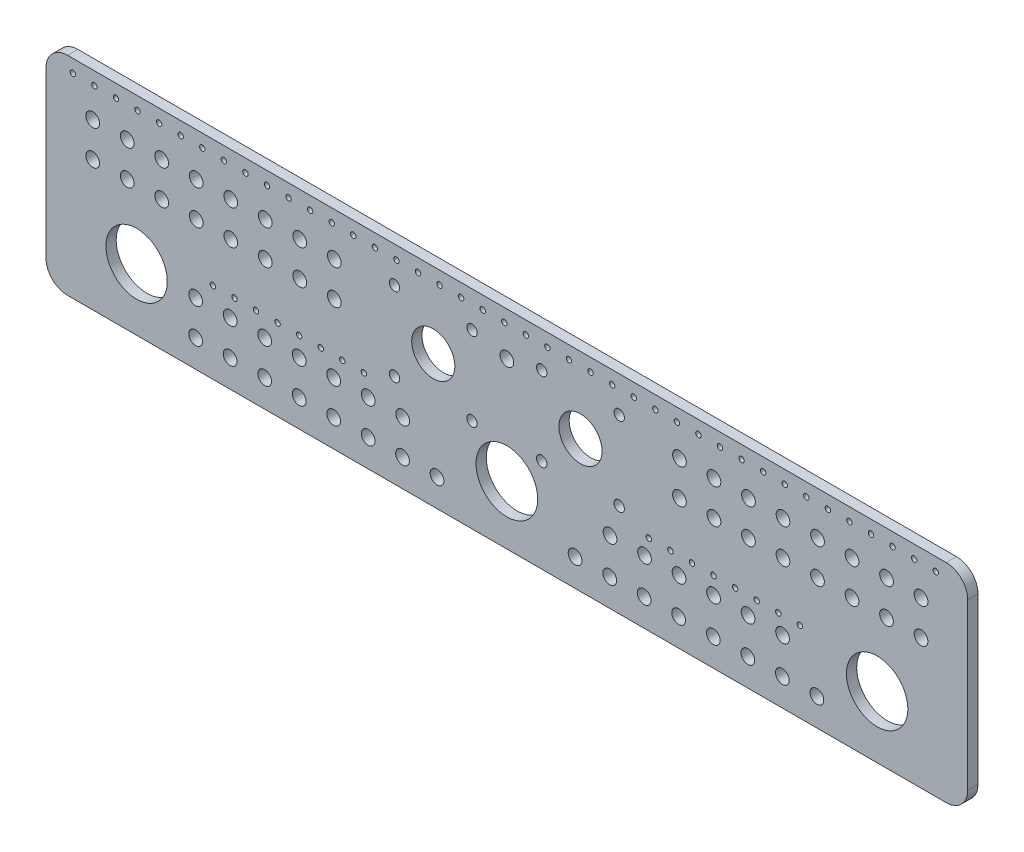
SolidWorks part; units mm, degrees
ref_plane "Front" through (0, 0, 0) normal (0, 0, 1) x (1, 0, 0)
ref_plane "Top" through (0, 0, 0) normal (0, 1, 0) x (1, 0, 0)
ref_plane "Right" through (0, 0, 0) normal (1, 0, 0) x (0, 0, -1)
sketch "Sketch1" plane through (0, 0, 0) normal (0, 0, 1) x (1, 0, 0)
  line L0 (-426.3498, 80.4904) -> (-19.0698, 80.4904)
  line L2 (-436.3498, 70.4904) -> (-436.3498, -5.9096)
  line L4 (-9.0698, 70.4904) -> (-9.0698, -5.9096)
  line L5 (-19.0698, -15.9096) -> (-426.3498, -15.9096)
  circle A0 centre (-394.3498, 12.7904) radius 14.225
  circle A1 centre (-51.0698, 12.7904) radius 14.225
  circle A11 centre (-222.7098, 11.2904) radius 14.3
  circle A54 centre (-174.8998, 13.3845) radius 3.18
  circle A151 centre (-366.9908, 12.7904) radius 3.18
  circle A155 centre (-358.9957, 21.7191) radius 1.25
  circle A159 centre (-94.8998, 13.3845) radius 3.18
  circle A181 centre (-366.9908, -3.2096) radius 3.18
  circle A190 centre (-94.9957, -3.2096) radius 3.18
  circle A191 centre (-110.9957, -3.2096) radius 3.18
  circle A192 centre (-126.9957, -3.2096) radius 3.18
  circle A193 centre (-78.9957, -3.2096) radius 3.18
  circle A194 centre (-143.0916, -3.2096) radius 3.18
  circle A195 centre (-159.0916, -3.2096) radius 3.18
  circle A196 centre (-174.9957, -3.2096) radius 3.18
  circle A279 centre (-96.8998, 21.3845) radius 1.25
  circle A285 centre (-106.8998, 21.3845) radius 1.25
  circle A286 centre (-350.9908, 12.7904) radius 3.18
  circle A287 centre (-350.9908, -3.2096) radius 3.18
  circle A288 centre (-334.9908, 12.7904) radius 3.18
  circle A289 centre (-334.9908, -3.2096) radius 3.18
  circle A290 centre (-318.9908, 12.7904) radius 3.18
  circle A291 centre (-318.9908, -3.2096) radius 3.18
  circle A292 centre (-302.9908, 12.7904) radius 3.18
  circle A293 centre (-302.9908, -3.2096) radius 3.18
  circle A294 centre (-286.9908, 12.7904) radius 3.18
  circle A295 centre (-286.9908, -3.2096) radius 3.18
  circle A296 centre (-158.8998, 13.3845) radius 3.18
  circle A297 centre (-142.8998, 13.3845) radius 3.18
  circle A298 centre (-126.8998, 13.3845) radius 3.18
  circle A299 centre (-110.8998, 13.3845) radius 3.18
  circle A309 centre (-86.8998, 21.3845) radius 1.25
  circle A314 centre (-270.9908, 12.7904) radius 3.18
  circle A328 centre (-348.9957, 21.7191) radius 1.25
  circle A361 centre (-116.8998, 21.3845) radius 1.25
  circle A362 centre (-338.9957, 21.7191) radius 1.25
  circle A363 centre (-328.9957, 21.7191) radius 1.25
  circle A364 centre (-318.9957, 21.7191) radius 1.25
  circle A365 centre (-308.9957, 21.7191) radius 1.25
  circle A366 centre (-298.9957, 21.7191) radius 1.25
  circle A367 centre (-288.9957, 21.7191) radius 1.25
  circle A378 centre (-126.8998, 21.3845) radius 1.25
  circle A379 centre (-136.8998, 21.3845) radius 1.25
  circle A380 centre (-146.8998, 21.3845) radius 1.25
  circle A381 centre (-156.8998, 21.3845) radius 1.25
  circle A402 centre (-213.9098, 74.4904) radius 1.25
  circle A441 centre (-30.7098, 60.4904) radius 3.18
  circle A447 centre (-414.7098, 60.4904) radius 3.18
  circle A448 centre (-203.9098, 74.4904) radius 1.25
  circle A449 centre (-193.9098, 74.4904) radius 1.25
  circle A450 centre (-183.9098, 74.4904) radius 1.25
  circle A451 centre (-173.9098, 74.4904) radius 1.25
  circle A452 centre (-163.9098, 74.4904) radius 1.25
  circle A453 centre (-153.9098, 74.4904) radius 1.25
  circle A454 centre (-143.9098, 74.4904) radius 1.25
  circle A455 centre (-133.9098, 74.4904) radius 1.25
  circle A456 centre (-123.9098, 74.4904) radius 1.25
  circle A457 centre (-113.9098, 74.4904) radius 1.25
  circle A458 centre (-103.9098, 74.4904) radius 1.25
  circle A459 centre (-93.9098, 74.4904) radius 1.25
  circle A460 centre (-83.9098, 74.4904) radius 1.25
  circle A461 centre (-73.9098, 74.4904) radius 1.25
  circle A462 centre (-63.9098, 74.4904) radius 1.25
  circle A463 centre (-53.9098, 74.4904) radius 1.25
  circle A464 centre (-43.9098, 74.4904) radius 1.25
  circle A465 centre (-33.9098, 74.4904) radius 1.25
  circle A466 centre (-23.9098, 74.4904) radius 1.25
  circle A469 centre (-223.9098, 74.4904) radius 1.25
  circle A470 centre (-233.9098, 74.4904) radius 1.25
  circle A471 centre (-243.9098, 74.4904) radius 1.25
  circle A472 centre (-253.9098, 74.4904) radius 1.25
  circle A473 centre (-263.9098, 74.4904) radius 1.25
  circle A474 centre (-273.9098, 74.4904) radius 1.25
  circle A475 centre (-283.9098, 74.4904) radius 1.25
  circle A476 centre (-293.9098, 74.4904) radius 1.25
  circle A477 centre (-303.9098, 74.4904) radius 1.25
  circle A478 centre (-313.9098, 74.4904) radius 1.25
  circle A479 centre (-323.9098, 74.4904) radius 1.25
  circle A480 centre (-333.9098, 74.4904) radius 1.25
  circle A481 centre (-343.9098, 74.4904) radius 1.25
  circle A482 centre (-353.9098, 74.4904) radius 1.25
  circle A483 centre (-363.9098, 74.4904) radius 1.25
  circle A484 centre (-373.9098, 74.4904) radius 1.25
  circle A485 centre (-383.9098, 74.4904) radius 1.25
  circle A486 centre (-393.9098, 74.4904) radius 1.25
  circle A487 centre (-403.9098, 74.4904) radius 1.25
  circle A488 centre (-413.9098, 74.4904) radius 1.25
  circle A520 centre (-191.0916, -3.2096) radius 3.18
  circle A524 centre (-255.0916, -3.2096) radius 3.18
  circle A525 centre (-223.0916, -3.2096) radius 3.18 [skipped]
  arc A538 (-426.3498, -15.9096) -> (-436.3498, -5.9096) centre (-426.3498, -5.9096) cw
  arc A539 (-426.3498, 80.4904) -> (-436.3498, 70.4904) centre (-426.3498, 70.4904) ccw
  arc A540 (-9.0698, 70.4904) -> (-19.0698, 80.4904) centre (-19.0698, 70.4904) ccw
  arc A541 (-9.0698, -5.9096) -> (-19.0698, -15.9096) centre (-19.0698, -5.9096) cw
  circle A552 centre (-423.9098, 74.4904) radius 1.25
  circle A554 centre (-222.7098, 60.4904) radius 3.18
  circle A555 centre (-271.0916, -3.2096) radius 3.18
  circle A570 centre (-256.8298, 45.4104) radius 10
  circle A583 centre (-274.7903, 27.4499) radius 2.413
  circle A584 centre (-238.8693, 27.4499) radius 2.413
  circle A585 centre (-274.7903, 63.965) radius 2.413
  circle A586 centre (-238.8693, 63.965) radius 2.413
  circle A592 centre (-188.5898, 45.4104) radius 10
  circle A593 centre (-206.5503, 63.965) radius 2.413
  circle A594 centre (-170.6293, 63.965) radius 2.413
  circle A595 centre (-170.6293, 27.4499) radius 2.413
  circle A596 centre (-206.5503, 27.4499) radius 2.413
  circle A597 centre (-278.9957, 21.7191) radius 1.25 [skipped]
  circle A598 centre (-166.8998, 21.3845) radius 1.25 [skipped]
  circle A599 centre (-238.9957, -3.2096) radius 3.18 [skipped]
  circle A600 centre (-206.9957, -3.2096) radius 3.18 [skipped]
  circle A601 centre (-86.8998, 1.3845) radius 1.25 [skipped]
  circle A602 centre (-96.8998, 1.3845) radius 1.25 [skipped]
  circle A603 centre (-116.8998, 1.3845) radius 1.25 [skipped]
  circle A604 centre (-106.8998, 1.3845) radius 1.25 [skipped]
  circle A605 centre (-126.8998, 1.3845) radius 1.25 [skipped]
  circle A606 centre (-136.8998, 1.3845) radius 1.25 [skipped]
  circle A607 centre (-146.8998, 1.3845) radius 1.25 [skipped]
  circle A608 centre (-156.8998, 1.3845) radius 1.25 [skipped]
  circle A609 centre (-166.8998, 1.3845) radius 1.25 [skipped]
  circle A610 centre (-278.9957, 1.7191) radius 1.25 [skipped]
  circle A611 centre (-288.9957, 1.7191) radius 1.25 [skipped]
  circle A612 centre (-298.9957, 1.7191) radius 1.25 [skipped]
  circle A613 centre (-308.9957, 1.7191) radius 1.25 [skipped]
  circle A614 centre (-318.9957, 1.7191) radius 1.25 [skipped]
  circle A615 centre (-328.9957, 1.7191) radius 1.25 [skipped]
  circle A616 centre (-338.9957, 1.7191) radius 1.25 [skipped]
  circle A617 centre (-348.9957, 1.7191) radius 1.25 [skipped]
  circle A618 centre (-358.9957, 1.7191) radius 1.25 [skipped]
  circle A627 centre (-398.7098, 60.4904) radius 3.18
  circle A628 centre (-382.7098, 60.4904) radius 3.18
  circle A629 centre (-366.7098, 60.4904) radius 3.18
  circle A630 centre (-350.7098, 60.4904) radius 3.18
  circle A631 centre (-334.7098, 60.4904) radius 3.18
  circle A632 centre (-318.7098, 60.4904) radius 3.18
  circle A633 centre (-302.7098, 60.4904) radius 3.18
  circle A634 centre (-398.7098, 44.4904) radius 3.18
  circle A635 centre (-382.7098, 44.4904) radius 3.18
  circle A636 centre (-366.7098, 44.4904) radius 3.18
  circle A637 centre (-350.7098, 44.4904) radius 3.18
  circle A638 centre (-334.7098, 44.4904) radius 3.18
  circle A639 centre (-318.7098, 44.4904) radius 3.18
  circle A640 centre (-302.7098, 44.4904) radius 3.18
  circle A641 centre (-414.7098, 44.4904) radius 3.18
  circle A645 centre (-46.7098, 60.4904) radius 3.18
  circle A646 centre (-62.7098, 60.4904) radius 3.18
  circle A647 centre (-78.7098, 60.4904) radius 3.18
  circle A648 centre (-94.7098, 60.4904) radius 3.18
  circle A649 centre (-110.7098, 60.4904) radius 3.18
  circle A650 centre (-126.7098, 60.4904) radius 3.18
  circle A651 centre (-142.7098, 60.4904) radius 3.18
  circle A652 centre (-46.7098, 44.4904) radius 3.18
  circle A653 centre (-62.7098, 44.4904) radius 3.18
  circle A654 centre (-78.7098, 44.4904) radius 3.18
  circle A655 centre (-94.7098, 44.4904) radius 3.18
  circle A656 centre (-110.7098, 44.4904) radius 3.18
  circle A657 centre (-126.7098, 44.4904) radius 3.18
  circle A658 centre (-142.7098, 44.4904) radius 3.18
  circle A659 centre (-30.7098, 44.4904) radius 3.18
  circle A664 centre (-3.9098, 74.4904) radius 1.25 [skipped]
  circle A667 centre (-423.9098, 74.4904) radius 1.25 [skipped]
  circle A668 centre (-13.9098, 74.4904) radius 1.25 [skipped]
  arc A669 (-270.9932, -6.3896) -> (-270.9932, -0.0296) centre (-270.9908, -3.2096) ccw [skipped]
  arc A670 (-270.9932, -6.3896) -> (-270.9932, -0.0296) centre (-270.9957, -3.2096) ccw [skipped]
  point P45 (-0.2698, -21.5096)
  point P52 (-0.2698, 90.4904)
  dimension "D2" = 42
  dimension "D4" = 42
  dimension "D6" = 222.44
  dimension "D8" = 12.7
  dimension "D12" = 171.64
  dimension "D13" = 22
  dimension "D14" = 10
  dimension "D15" = 10
  dimension "D16" = 2
  dimension "D17" = 10
  dimension "D21" = 2
  dimension "D23" = 8
  dimension "D27" = 2
  dimension "D28" = 20
  dimension "D29" = 14
  dimension "D30" = 2
  dimension "D24" = 2
  dimension "D10" = 34.12
  dimension "D18" = 4
  dimension "D25" = 171.64
  dimension "D35" = 2
  dimension "D36" = 17.9605
  dimension "D26" = 10
  dimension "D1" = 112
  dimension "D5" = 16
  dimension "D7" = 6
  dimension "D9" = 5
  dimension "D11" = 22
  dimension "D19" = 8
  dimension "D20" = 9
  dimension "D22" = 2
  dimension "D34" = 34.12
  dimension "D37" = 17.9605
  dimension "D38" = 17.9605
extrude "Boss-Extrude5" add sketch "Sketch1" along normal blind 4.7625
move or copy body "Body-Move/Copy1" [suppressed]
